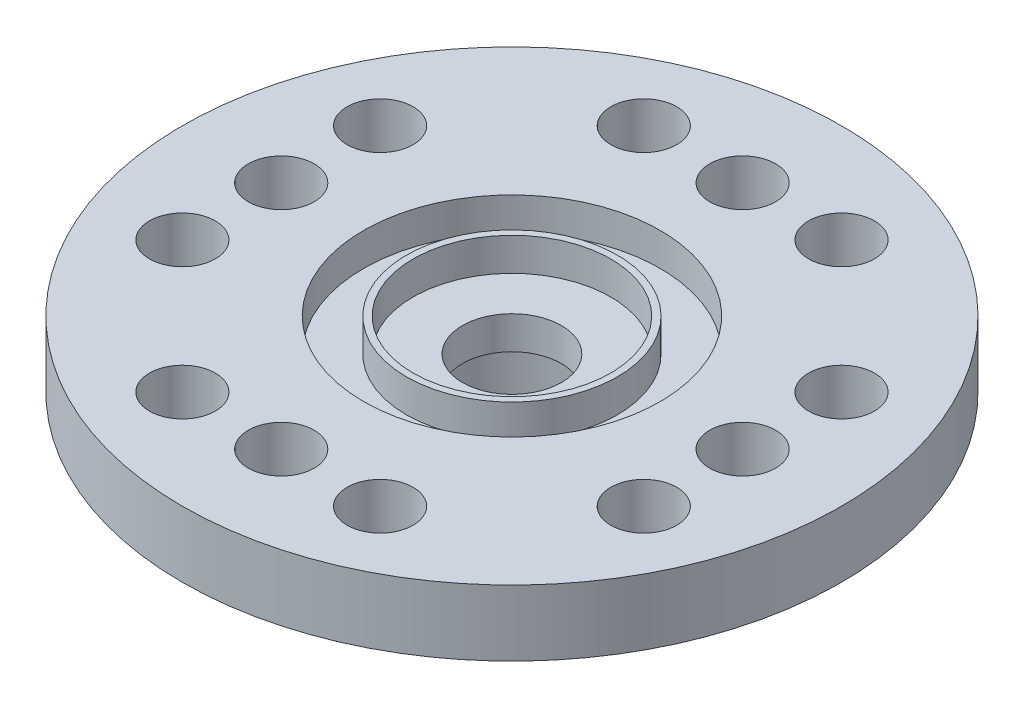
SolidWorks part; units mm, degrees
ref_plane "Front Plane" through (0, 0, 0) normal (0, 0, 1) x (1, 0, 0)
ref_plane "Top Plane" through (0, 0, 0) normal (0, 1, 0) x (1, 0, 0)
ref_plane "Right Plane" through (0, 0, 0) normal (1, 0, 0) x (0, 0, -1)
sketch "Sketch1" plane through (0, 0, 0) normal (0, 1, 0) x (1, 0, 0)
  circle A0 centre (0, 0) radius 4
  circle A1 centre (0, 0) radius 3
  dimension "D1" = 8
  dimension "D2" = 1
extrude "Boss-Extrude1" add sketch "Sketch1" along normal blind 3
sketch "Sketch2" plane through (0, 3, 0) normal (0, 1, 0) x (1, 0, 0)
  circle A0 centre (0, 0) radius 10
  dimension "D1" = 20
extrude "Boss-Extrude2" add sketch "Sketch2" along normal blind 2
sketch "Sketch3" plane through (0, 5, 0) normal (0, 1, 0) x (1, 0, 0)
  line L0 (-3.3571, 7) -> (3.3571, 7) construction
  line L1 (7, 3.2198) -> (7, -3.2198) construction
  line L2 (-4.3948, -7) -> (4.3948, -7) construction
  line L3 (-7, 3.7386) -> (-7, -3.7386) construction
  circle A0 centre (0, 0) radius 7 construction
  circle A1 centre (0, 7) radius 1
  circle A2 centre (3, 7) radius 1
  circle A3 centre (-3, 7) radius 1
  circle A4 centre (7, 3) radius 1
  circle A5 centre (7, 0) radius 1
  circle A6 centre (7, -3) radius 1
  circle A7 centre (3, -7) radius 1
  circle A8 centre (0, -7) radius 1
  circle A9 centre (-3, -7) radius 1
  circle A10 centre (-7, -3) radius 1
  circle A11 centre (-7, 0) radius 1
  circle A12 centre (-7, 3) radius 1
  circle A13 centre (0, 0) radius 1.5
  point P6 (0, 7)
  point P9 (7, 0)
  point P12 (0, -7)
  point P15 (-7, 0)
  dimension "D1" = 2
  dimension "D6" = 3
  dimension "D2" = 7
  dimension "D3" = 3
  dimension "D4" = 3
  dimension "D5" = 4
extrude "Cut-Extrude1" cut sketch "Sketch3" against normal up to next
sketch "Sketch4" plane through (0, 5, 0) normal (0, 1, 0) x (1, 0, 0)
  circle A0 centre (0, 0) radius 4.5
  circle A1 centre (0, 0) radius 3
  circle A2 centre (0, 0) radius 3.2
  circle M6 centre (0, 0) radius 1.5
  dimension "D1" = 9
  dimension "D2" = 6
  dimension "D3" = 0.2
extrude "Cut-Extrude2" cut sketch "Sketch4" against normal blind 1 contours A0 A2 | A1 M6
